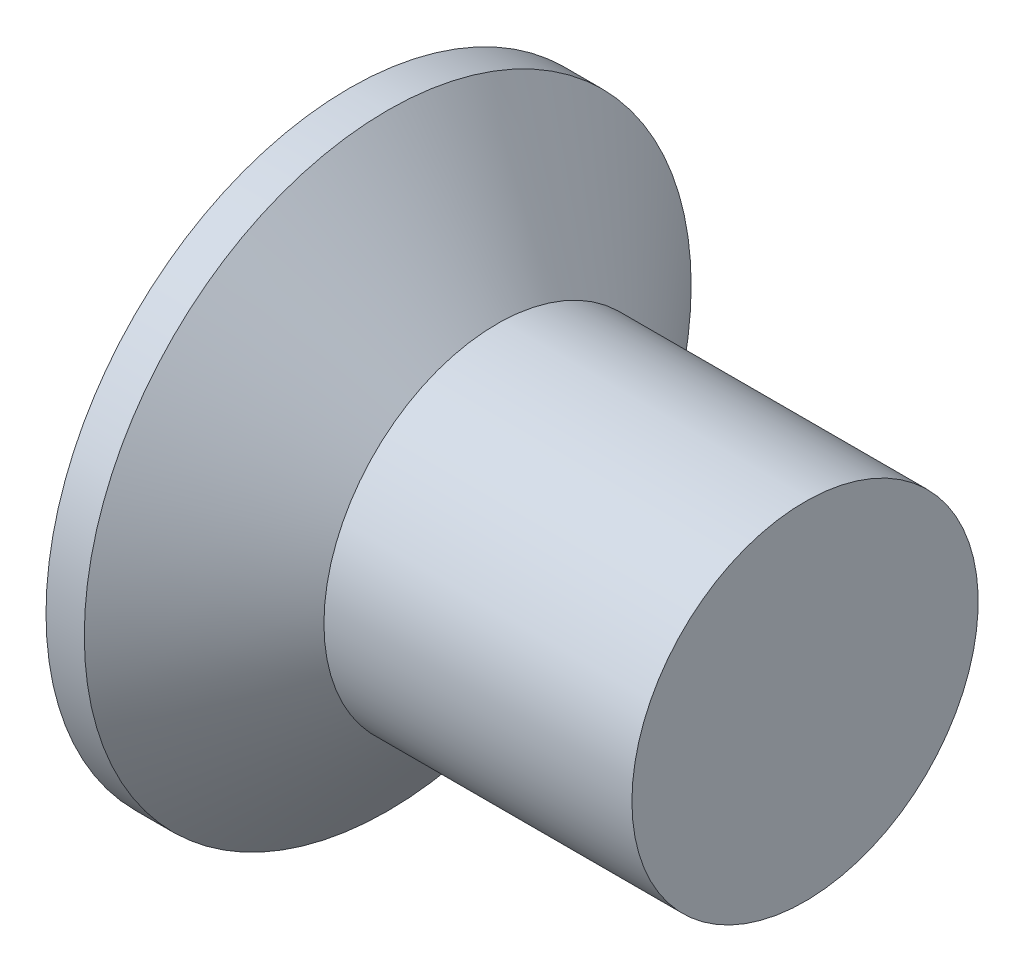
SolidWorks part; units mm, degrees
revolve "Base-Revolve" add sketch "BodySke" angle 360 about L5
sketch "BodySke" plane through (0, 0, 0) normal (0, 0, 1) x (1, 0, 0)
  line L0 (0, 0) -> (0, 4.2291)
  line L1 (0, 4.2291) -> (0.5335, 4.2291)
  line L2 (2.0574, 2.413) -> (6.35, 2.413)
  line L3 (6.35, 2.413) -> (6.35, 0)
  line L4 (6.35, 0) -> (0, 0)
  line L5 (-6.35, 0) -> (82.55, 0) construction
  line L6 (2.0574, -2.413) -> (6.35, -2.413) construction
  line L7 (0.5335, -4.2291) -> (2.0574, -2.413) construction
  line L8 (0.5335, 4.2291) -> (2.0574, 2.413)
  line L9 (0, -4.2291) -> (0.5335, -4.2291) construction
  line L10 (2.8499, 4.0005) -> (2.8499, -5.5245) construction
  line L11 (0, 6.35) -> (0, -3.175) construction
  dimension "Diameter" = 4.826
  dimension "Length" = 6.35
  dimension "Head_ht" = 2.0574
  dimension "Head_dia" = 8.4582
  dimension "Head_ang" = 100
  dimension "D6" = 0.5335
  dimension "Advance" = 0.7925
  dimension "Thread_nom" = 6.35
cosmetic thread "ThreadCosmetic" [suppressed] parameters "Thread_length"=22.5501, "Thread_minor"=3.8811
extrude "Slot" [suppressed] cut sketch "Sketch2" against normal blind 1.0668
sketch "Sketch2" plane through (0, 0, 0) normal (-1, 0, 0) x (0, 0, 1)
  line L0 (-4.2291, -0.762) -> (4.2291, -0.762)
  line L1 (-4.2291, -0.762) -> (-4.2291, 0.762)
  line L2 (4.2291, 0.762) -> (-4.2291, 0.762)
  line L3 (4.2291, 0.762) -> (4.2291, -0.762)
  dimension "Slot_width" = 1.524
  dimension "D1" = 0.762
  dimension "D2" = 8.4582
  dimension "D3" = 4.2291
ref_plane "Plane1" through (0, 0, 0) normal (0, 0, 1) x (1, 0, 0)
ref_plane "Plane2" through (0, 0, 0) normal (0, 1, 0) x (1, 0, 0)
ref_plane "Plane3" through (0, 0, 0) normal (1, 0, 0) x (0, 0, -1)
sketch "Sketch3" plane through (0, 0, 0) normal (-1, 0, 0) x (0, 0, 1)
  line L0 (-0.5334, 2.8575) -> (0.5334, 2.8575)
  line L1 (0.5334, 2.8575) -> (0.5334, -2.8575)
  line L2 (0.5334, -2.8575) -> (-0.5334, -2.8575)
  line L3 (-0.5334, -2.8575) -> (-0.5334, 2.8575)
  dimension "Cross_dia" = 5.715
  dimension "Cross_width" = 1.0668
  dimension "D1" = 2.8575
  dimension "D2" = 0.5334
ref_plane "Plane4" through (3.7338, 0, 0) normal (-1, 0, 0) x (0, 0, 1)
sketch "Sketch4" plane through (3.7338, 0, 0) normal (-1, 0, 0) x (0, 0, 1)
  line L0 (-0.2667, 0.2667) -> (0.2667, 0.2667)
  line L3 (0.2667, 0.2667) -> (0.2667, -0.2667)
  line L4 (0.2667, -0.2667) -> (-0.2667, -0.2667)
  line L5 (-0.2667, -0.2667) -> (-0.2667, 0.2667)
  dimension "D2" = 0.5334
  dimension "D1" = 0.5334
  dimension "D3" = 0.2667
  dimension "D4" = 0.2667
loft "Cross" cut profiles "Sketch3", "Sketch4"
pattern_circular "CirPattern1" count 2 every 90 about axis through (0, 0, 0) along (1, 0, 0) of "Cross"
sketch "ThdSchSke" plane through (0, 0, 0) normal (0, 0, 1) x (1, 0, 0)
  line L0 (2.8499, -1.9406) -> (2.5191, -2.413)
  line L1 (2.8499, -1.9406) -> (3.1807, -2.413)
  line L2 (3.1807, -2.413) -> (3.1807, -3.0163)
  line L3 (-3.175, 0) -> (5.1513, 0) construction
  line L5 (3.1807, -3.0163) -> (2.5191, -3.0163)
  line L6 (2.5191, -3.0163) -> (2.5191, -2.413)
  line L7 (0, 4.2291) -> (0, -4.2291) construction
  dimension "Diameter" = 4.826
  dimension "Thread_minor" = 3.8811
  dimension "Start" = 2.8499
revolve "ThreadSchematic" [suppressed] cut sketch "ThdSchSke" angle 360 about L3
pattern_linear "ThdSchPat" [suppressed]
equation "\"D1@Sketch3\" = \"Cross_dia@Sketch3\" / 2"
equation "\"D2@Sketch3\" = \"Cross_width@Sketch3\" / 2"
equation "\"D1@Sketch4\" = \"Cross_width@Sketch3\" *.5"
equation "\"D2@Sketch4\" = \"D1@Sketch4\""
equation "\"D4@Sketch4\" = \"D2@Sketch4\" / 2"
equation "\"D3@Sketch4\" = \"D1@Sketch4\" / 2"
equation "\"D1@Sketch2\" = \"Slot_width@Sketch2\" / 2"
equation "\"D2@Sketch2\" = \"Head_dia@BodySke\""
equation "\"D3@Sketch2\" = \"D2@Sketch2\" / 2"
equation "\"Thread_length@ThreadCosmetic\" = ((sgn( (\"Length@BodySke\" - \"Advance@BodySke\" - \"Head_ht@BodySke\" ) - \"Thread_nom@BodySke\" )-1)*( (\"Length@BodySke\" - \"Advance@BodySke\" - \"Head_ht@BodySke\" ) - \"Thread_nom@BodySke\" ))/-2+ \"Thread_nom@BodySke\""
equation "\"Thread_minor@ThdSchSke\" = \"Thread_minor@ThreadCosmetic\""
equation "\"Diameter@ThdSchSke\" = \"Diameter@BodySke\""
equation "\"Overcut@ThdSchSke\" = \"Diameter@BodySke\" * 1.25"
equation "\"Start@ThdSchSke\" = 0.000001 + \"Length@BodySke\" - \"Thread_length@ThreadCosmetic\"  '---Countersunk---"
equation "\"Num_threads@ThdSchPat\" = int( \"Thread_length@ThreadCosmetic\" / \"Advance@BodySke\" + 0.999 )  + 1"
equation "\"Advance@ThdSchPat\" = \"Thread_length@ThreadCosmetic\" /  (\"Num_threads@ThdSchPat\" - 1) 'relax it"
